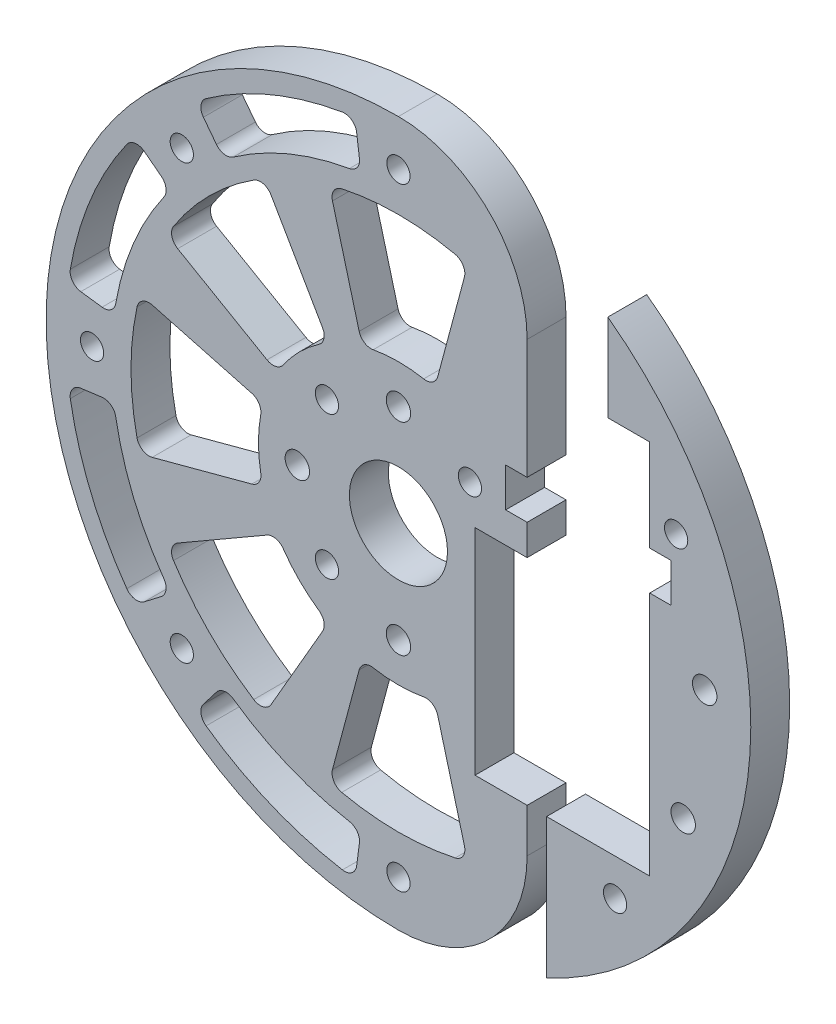
SolidWorks part; units mm, degrees
material "Balsa"
ref_plane "Front Plane" through (0, 0, 0) normal (0, 0, 1) x (1, 0, 0)
ref_plane "Top Plane" through (0, 0, 0) normal (0, 1, 0) x (1, 0, 0)
ref_plane "Right Plane" through (0, 0, 0) normal (1, 0, 0) x (0, 0, -1)
sketch "Sketch1" plane through (0, 0, 0) normal (0, 0, 1) x (1, 0, 0)
  line L0 (45.3154, 21.1309) -> (0, 0) construction
  line L1 (0, 0) -> (35.3553, -35.3553) construction
  line L2 (49.9788, 1.4542) -> (0, 0) construction
  line L3 (0, 0) -> (46.4674, -18.4603) construction
  circle A0 centre (45.3154, 21.1309) radius 1.8986
  circle A1 centre (49.9788, 1.4542) radius 1.9939
  circle A2 centre (0, 0) radius 57.5
  circle A3 centre (0, 0) radius 8
  circle A4 centre (0, 0) radius 16.5 construction
  circle A5 centre (46.4674, -18.4603) radius 1.9939
  circle A6 centre (0, 0) radius 50 construction
  circle A27 centre (0, -16.5) radius 1.9939
  circle A28 centre (11.6673, -11.6673) radius 1.8986 construction
  circle A30 centre (0, -50) radius 1.8986
  circle A31 centre (-16.5, 0) radius 1.9939
  circle A32 centre (-11.6673, -11.6673) radius 1.8986
  circle A33 centre (0, 16.5) radius 1.9939
  circle A34 centre (-11.6673, 11.6673) radius 1.8986
  circle A35 centre (16.5, 0) radius 1.9939 construction
  circle A36 centre (11.6673, 11.6673) radius 1.8986
  circle A38 centre (-35.3553, -35.3553) radius 1.8986
  circle A40 centre (-50, 0) radius 1.8986
  circle A42 centre (-35.3553, 35.3553) radius 1.8986
  circle A44 centre (0, 50) radius 1.8986
  circle A46 centre (35.3553, 35.3553) radius 1.8986 construction
  circle A48 centre (50, 0) radius 1.8986 construction
  circle A50 centre (35.3553, -35.3553) radius 1.8986
  dimension "D1" = 115
  dimension "D4" = 70
  dimension "D6" = 100
  dimension "D7" = 23.333
  dimension "D8" = 33
  dimension "D9" = 3.7973
  dimension "D10" = 3.9878
  dimension "D15" = 3.7973
  dimension "D17" = 3.9878
  dimension "D18" = 3.7973
  dimension "D3" = 16
  dimension "D11" = 3.9878
  dimension "D5" = 23.333
  dimension "D19" = 45
  dimension "D20" = 4
  dimension "D21" = 8
extrude "Boss-Extrude1" add sketch "Sketch1" along normal blind 6.35
sketch "Sketch2" plane through (0, 0, 0) normal (0, 0, 1) x (1, 0, 0)
  line L0 (12.5, -29.35) -> (41, -29.35)
  line L1 (41, -29.35) -> (41, 10.65)
  line L2 (41, 10.65) -> (44.5, 10.65)
  line L3 (44.5, 10.65) -> (44.5, 17)
  line L4 (44.5, 17) -> (41, 17)
  line L5 (41, 17) -> (41, 32)
  line L6 (41, 32) -> (21, 32)
  line L7 (21, 32) -> (21, 17)
  line L8 (21, 17) -> (17.5, 17)
  line L9 (17.5, 17) -> (17.5, 10.65)
  line L10 (17.5, 10.65) -> (21, 10.65)
  line L11 (21, 10.65) -> (21, 5.65)
  line L12 (21, 5.65) -> (12.5, 5.65)
  line L13 (12.5, 5.65) -> (12.5, -29.35)
  dimension "D1" = 20
  dimension "D2" = 3.5
  dimension "D3" = 3.5
  dimension "D4" = 15
  dimension "D5" = 6.35
  dimension "D6" = 5
  dimension "D7" = 40
  dimension "D8" = 8.5
  dimension "D9" = 32
  dimension "D10" = 21
extrude "Cut-Extrude1" cut sketch "Sketch2" along normal through all
sketch "Sketch3" plane through (0, 0, 0) normal (0, 0, -1) x (-1, 0, 0)
  line L0 (-41, 32) -> (-21, 32) construction
  line L1 (-34.175, -8) -> (-27.825, -8)
  line L2 (-34.175, -8) -> (-34.175, 72)
  line L3 (-34.175, 72) -> (-27.825, 72)
  line L4 (-27.825, -8) -> (-27.825, 72)
  line L5 (-34.175, -8) -> (-27.825, 72) construction
  line L6 (-34.175, 72) -> (-27.825, -8) construction
  point P0 (-31, 32)
  dimension "D1" = 6.35
  dimension "D2" = 80
extrude "Cut-Extrude3" cut sketch "Sketch3" against normal through all
sketch "Sketch4" plane through (0, 0, 0) normal (0, 0, 1) x (1, 0, 0)
  line L0 (21, -36.5) -> (21, -5.3721)
  line L1 (21, -5.3721) -> (24.175, -5.4115)
  line L2 (24.175, -5.4115) -> (24.175, -57.5)
  line L3 (0, -57.5) -> (24.175, -57.5)
  line L4 (0, 0) -> (82.9328, 0) construction
  line L5 (34.175, 32) -> (27.825, 32) construction
  line L6 (0, 57.5) -> (24.175, 57.5)
  line L7 (24.175, 5.4115) -> (24.175, 57.5)
  line L8 (21, 5.3721) -> (24.175, 5.4115)
  line L9 (21, 36.5) -> (21, 5.3721)
  arc A0 (0, -57.5) -> (21, -36.5) centre (0, -36.5) ccw
  arc A1 (0, 57.5) -> (21, 36.5) centre (0, 36.5) cw
  arc A2 (27.825, 50.3192) -> (34.175, 46.242) centre (0, 0) ccw construction
  point P13 (31, 32)
  point P16 (22.5875, -5.3918)
  dimension "D2" = 3.175
  dimension "D4" = 8.4125
extrude "Cut-Extrude5" cut sketch "Sketch4" along normal through all
sketch "Sketch5" plane through (0, 0, 6.35) normal (0, 0, 1) x (1, 0, 0)
  line L3 (24.175, 52.1711) -> (24.175, 32)
  line L4 (24.175, 32) -> (27.825, 32)
  line L5 (27.825, 32) -> (27.825, 50.3192)
  line L6 (24.175, 52.1711) -> (24.175, 32)
  line L7 (24.175, 32) -> (27.825, 32)
  line L8 (27.825, 32) -> (27.825, 50.3192)
  arc A1 (27.825, 50.3192) -> (24.175, 52.1711) centre (0, 0) ccw
  arc A2 (27.825, 50.3192) -> (24.175, 52.1711) centre (0, 0) ccw
  dimension "D1" = 0
extrude "Cut-Extrude6" cut sketch "Sketch5" against normal through all
sketch "Sketch6" plane through (0, 0, 6.35) normal (0, 0, 1) x (1, 0, 0)
  line L0 (0, 0) -> (-85.7599, 0) construction
  line L1 (-42.1627, -11.2975) -> (-22.0714, -5.914)
  line L2 (-42.1627, 11.2975) -> (-22.0714, 5.914)
  arc A0 (-22.0714, -5.914) -> (-22.0714, 5.914) centre (0, 0) cw
  arc A1 (-42.1627, -11.2975) -> (-42.1627, 11.2975) centre (0, 0) cw
  circle A2 centre (-16.5, 0) radius 1.9939 construction
  circle A3 centre (-50, 0) radius 1.8987 construction
  point P7 (-22.85, 0)
  point P8 (-43.65, 0)
  dimension "D1" = 6.35
  dimension "D2" = 6.35
  dimension "D3" = 30
extrude "Cut-Extrude7" cut sketch "Sketch6" against normal through all
fillet "Fillet1" radius 2 4 edges at (-42.1627, -11.2975, 3.175) (-22.0714, -5.914, 3.175) (-22.0714, 5.914, 3.175) (-42.1627, 11.2975, 3.175)
pattern_circular "CirPattern1" count 8 over 360 about axis through (0, 0, 0) along (0, 0, 1) skipping 3, 4, 5 of "Fillet1", "Cut-Extrude7"
sketch "Sketch7" plane through (0, 0, 6.35) normal (0, 0, 1) x (1, 0, 0)
  line L0 (0, 0) -> (-92.6914, 0) construction
  line L1 (0, 0) -> (-89.5535, 37.0943) construction
  line L2 (-43.0989, 33.071) -> (-37.1488, 28.5053)
  line L4 (-53.8602, 7.0908) -> (-46.4244, 6.1119)
  arc A0 (-53.8602, 7.0908) -> (-43.0989, 33.071) centre (0, 0) cw
  arc A1 (-46.4244, 6.1119) -> (-37.1488, 28.5053) centre (0, 0) cw
  circle A2 centre (-50, 0) radius 1.8987 construction
  circle A3 centre (-50, 0) radius 1.8986 construction
  arc A4 (-42.6565, 9.2598) -> (-42.6565, -9.2598) centre (0, 0) ccw construction
  arc A5 (0, 57.5) -> (0, -57.5) centre (0, 0) ccw construction
  point P11 (-43.2607, 17.9192)
  dimension "D3" = 3.175
  dimension "D4" = 3.175
  dimension "D1" = 22.5
  dimension "D2" = 30
extrude "Cut-Extrude8" cut sketch "Sketch7" against normal through all
fillet "Fillet2" radius 2 4 edges at (-53.8602, 7.0908, 3.175) (-46.4244, 6.1119, 3.175) (-37.1488, 28.5053, 3.175) (-43.0989, 33.071, 3.175)
pattern_circular "CirPattern2" count 8 over 360 about axis through (0, 0, 0) along (0, 0, 1) skipping 2, 3, 4, 5 of "Cut-Extrude8", "Fillet2"
